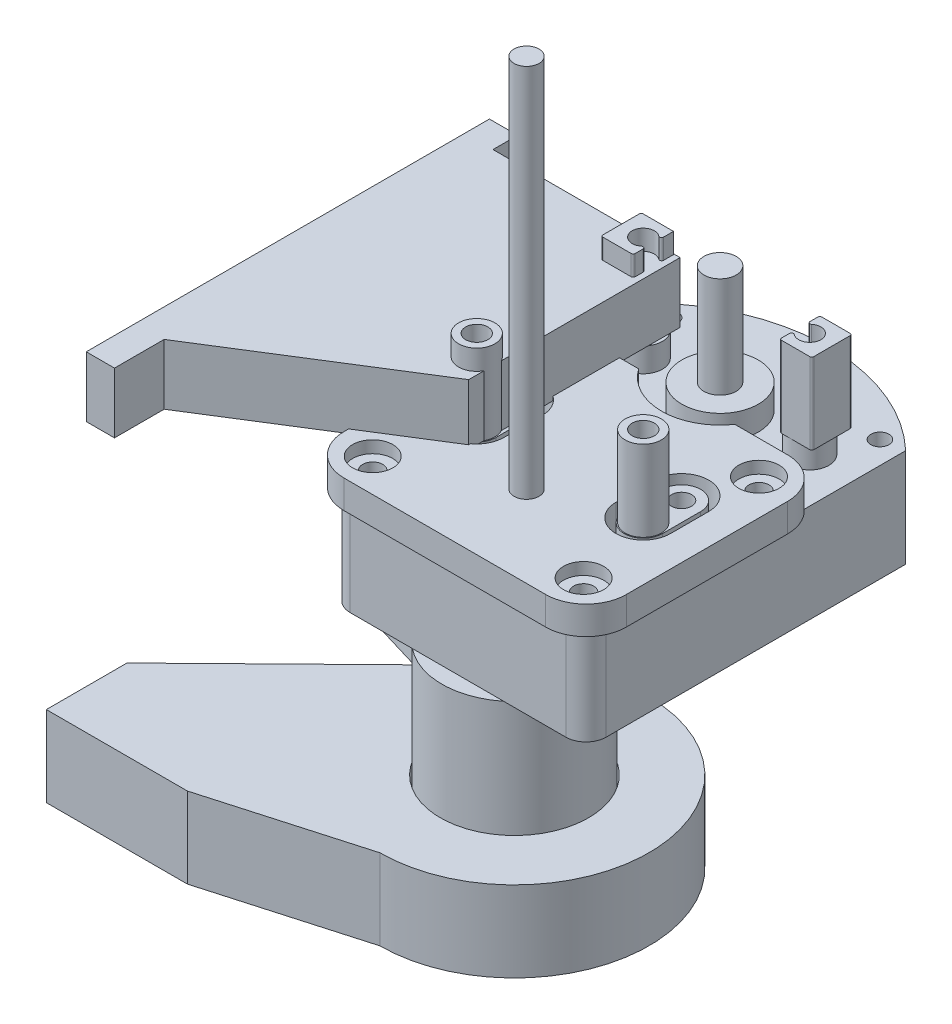
SolidWorks part; units mm, degrees
other "Gearbox Spacer rectangle"
other "Gearbox Spacer round "
ref_plane "Front Plane" through (0, 0, 0) normal (0, 0, 1) x (1, 0, 0)
ref_plane "Top Plane" through (0, 0, 0) normal (0, 1, 0) x (1, 0, 0)
ref_plane "Right Plane" through (0, 0, 0) normal (1, 0, 0) x (0, 0, -1)
sketch "Sketch1" plane through (0, 0, 0) normal (0, 1, 0) x (1, 0, 0)
  line L0 (31.75, -46) -> (31.75, 46)
  line L1 (31.75, -46) -> (-31.75, -46)
  line L2 (31.75, -46) -> (31.75, 46)
  line L3 (31.75, 46) -> (-31.75, 46)
  line L4 (-31.75, -46) -> (-31.75, 46)
  line L5 (0, 46) -> (0, -46) construction
  line L6 (31.75, 0) -> (-31.75, 0) construction
  line L7 (-31.75, -46) -> (-31.75, 46)
  circle A0 centre (-26.15, -41) radius 2.25
  circle A1 centre (-26.15, 2.5) radius 2.25
  circle A2 centre (-26.15, 32.5) radius 2.25
  circle A3 centre (26.15, 32.5) radius 2.25
  circle A4 centre (26.15, 2.5) radius 2.25
  circle A5 centre (26.15, -41) radius 2.25
  point P0 (0, 0)
  dimension "D3" = 4.5
  dimension "D1" = 63.5
  dimension "D2" = 92
  dimension "D4" = 52.3
  dimension "D5" = 5
  dimension "D6" = 43.5
  dimension "D7" = 30
extrude "Boss-Extrude1" add sketch "Sketch1" along normal blind 24.4 contours L4 L1 L0 L3 A4 A0 A1 A2 A3 A5
sketch "Sketch2" plane through (0, 24.4, 0) normal (0, 1, 0) x (1, 0, 0)
  line L0 (-20.65, -11.2) -> (-20.65, -20.7) construction
  line L1 (-15.9, -11.2) -> (-15.9, -20.7)
  line L2 (-25.4, -11.2) -> (-25.4, -20.7)
  line L3 (0, 0) -> (0, 46) construction
  line L4 (31.75, 46) -> (-31.75, 46) construction
  line L5 (0, 0) -> (-31.75, 0) construction
  line L6 (-31.75, -46) -> (-31.75, 46) construction
  line L7 (31.75, -46) -> (-31.75, -46) construction
  line L8 (20.65, -11.2) -> (20.65, -20.7) construction
  line L9 (15.9, -11.2) -> (15.9, -20.7)
  line L10 (25.4, -11.2) -> (25.4, -20.7)
  arc A0 (-15.9, -11.2) -> (-25.4, -11.2) centre (-20.65, -11.2) ccw
  arc A1 (-25.4, -20.7) -> (-15.9, -20.7) centre (-20.65, -20.7) ccw
  circle A2 centre (-20.65, 20.6) radius 4.75
  circle A3 centre (-20.65, -11.2) radius 2.5
  circle A4 centre (-20.65, -20.7) radius 2.5
  circle A5 centre (-20.65, 20.6) radius 2.5
  circle A6 centre (0, 19) radius 9.5
  circle A7 centre (0, 19) radius 4
  circle A8 centre (20.65, 20.6) radius 2.5
  circle A9 centre (20.65, -20.7) radius 2.5
  circle A10 centre (20.65, -11.2) radius 2.5
  circle A11 centre (20.65, 20.6) radius 4.75
  arc A12 (15.9, -11.2) -> (25.4, -11.2) centre (20.65, -11.2) cw
  arc A13 (25.4, -20.7) -> (15.9, -20.7) centre (20.65, -20.7) cw
  point P2 (-20.65, -15.95)
  point P39 (20.65, -15.95)
  dimension "D1" = 65
  dimension "D7" = 8
  dimension "D8" = 19
  dimension "D9" = 5
  dimension "D10" = 9.5
  dimension "D11" = 4.75
  dimension "D2" = 41.3
  dimension "D3" = 9.5
  dimension "D4" = 31.8
  dimension "D5" = 1.6
  dimension "D6" = 27
extrude "Boss-Extrude2" add sketch "Sketch2" along normal blind 6
sketch "Sketch3" plane through (0, 24.4, 0) normal (0, 1, 0) x (1, 0, 0)
  circle A1 centre (0, 19) radius 4
  circle A2 centre (0, 19) radius 4
  dimension "D1" = 0
extrude "Boss-Extrude3" add sketch "Sketch3" along normal blind 31
fillet "Fillet1" radius 5 2 edges at (31.75, 12.2, 46) (-31.75, 12.2, 46)
sketch "Sketch5" plane through (0, 24.4, 0) normal (0, 1, 0) x (1, 0, 0)
  line L0 (-31.75, -29) -> (31.75, -29) construction
  line L4 (31.75, -41) -> (31.75, 46) construction
  line L5 (-31.75, -41) -> (-31.75, 46) construction
  circle A0 centre (0, -29) radius 3.1
  circle A1 centre (0, 19) radius 15 construction
  circle A2 centre (0, -29) radius 33 construction
  dimension "D1" = 6.2
  dimension "D2" = 66
  dimension "D3" = 30
extrude "Boss-Extrude4" add sketch "Sketch5" along normal blind 100 separate body
sketch "Sketch6" plane through (0, 0, 0) normal (0, -1, 0) x (1, 0, 0)
  line L0 (-21.8301, 50) -> (22.1571, 50) construction
  line L1 (31.75, -46) -> (-31.75, -46) construction
  line L2 (0, 0) -> (0, 46) construction
  line L3 (26.75, 46) -> (-26.75, 46) construction
  circle A0 centre (0, 32) radius 18
  dimension "D1" = 96
  dimension "D2" = 36
extrude "Boss-Extrude5" add sketch "Sketch6" along normal blind 57
sketch "Sketch7" plane through (0, 24.4, 0) normal (0, 1, 0) x (1, 0, 0)
  line L1 (31.75, 33.2857) -> (31.75, 46)
  line L2 (31.75, -41) -> (31.75, 46) construction
  line L5 (-26.75, -46) -> (26.75, -46)
  line L6 (31.75, -41) -> (31.75, 46)
  line L7 (31.75, 46) -> (-31.75, 46)
  line L8 (-31.75, 46) -> (-31.75, -41)
  line L11 (31.75, 46) -> (-31.75, 46)
  line L12 (-31.75, 46) -> (-31.75, 33.2857)
  arc A1 (31.75, 33.2857) -> (-31.75, 33.2857) centre (0, 0) ccw
  arc A3 (26.75, -46) -> (31.75, -41) centre (26.75, -41) ccw
  arc A4 (-31.75, -41) -> (-26.75, -46) centre (-26.75, -41) ccw
  line M22 (31.75, -41) -> (31.75, 46)
  line M23 (31.75, 46) -> (-31.75, 46)
  line M24 (-31.75, 46) -> (-31.75, -41)
  dimension "D1" = 0
extrude "Cut-Extrude1" cut sketch "Sketch7" against normal up to next (24.4 mm away) contours A1 L11 M24 | A1 M22 M23
sketch "Sketch8" plane through (0, 30.4, 0) normal (0, 1, 0) x (1, 0, 0)
  line L0 (-16.6991, 25.7895) -> (-16.6991, -26.6457)
  line L1 (-16.6991, -26.6457) -> (-63.11, -55.7757)
  line L2 (-63.11, -55.7757) -> (-63.11, -68.0986)
  line L3 (-63.11, -68.0986) -> (-70.11, -68.0986)
  line L4 (-70.11, -68.0986) -> (-70.11, 31.9014)
  line L5 (-70.11, 31.9014) -> (-63.11, 31.9014)
  line L6 (-63.11, 31.9014) -> (-63.11, 25.7895)
  line L7 (-63.11, 25.7895) -> (-16.6991, 25.7895)
  line L8 (-31.75, -41) -> (-31.75, 33.2857) construction
  dimension "D1" = 38.36
  dimension "D2" = 7
  dimension "D3" = 100
extrude "Boss-Extrude6" add sketch "Sketch8" along normal blind 15 separate body
ref_plane "Plane1" through (0, -28.5, 0) normal (0, -1, 0) x (-1, 0, 0)
sketch "Sketch9" plane through (0, -28.5, 0) normal (0, -1, 0) x (-1, 0, 0)
  line L0 (25.1492, -10.0586) -> (72.11, -56)
  line L1 (72.11, -56) -> (72.11, -76)
  line L2 (72.11, -76) -> (37.11, -76)
  line L3 (72.11, 24) -> (72.11, 4)
  line L4 (37.11, -76) -> (0, -65.4)
  line L5 (72.11, 4) -> (25.1492, -10.0586)
  line L6 (72.11, 24) -> (42.2816, 24)
  line L7 (42.2816, 24) -> (0, 1.4)
  circle A0 centre (0, -32) radius 18.4
  arc A1 (0, 1.4) -> (0, -65.4) centre (0, -32) ccw
  circle A2 centre (0, -32) radius 18 construction
  dimension "D1" = 0.4
  dimension "D2" = 15
  dimension "D3" = 72.11
  dimension "D4" = 44
  dimension "D5" = 35
  dimension "D6" = 20
  dimension "D7" = 36
  dimension "D8" = 20
extrude "Boss-Extrude7" add sketch "Sketch9" along normal blind 20 separate body
sketch "Sketch11" plane through (0, 24.4, 0) normal (0, 1, 0) x (1, 0, 0)
  circle A0 centre (-26.15, 2.5) radius 4.85
  circle A1 centre (26.15, 2.5) radius 4.85
  circle A2 centre (-26.15, -41) radius 4.85
  circle A3 centre (26.15, -41) radius 4.85
  circle A4 centre (26.15, 2.5) radius 2.25 construction
  circle A5 centre (26.15, -41) radius 2.25 construction
  circle A6 centre (-26.15, -41) radius 2.25 construction
  circle A7 centre (-26.15, 2.5) radius 2.25 construction
  circle A8 centre (26.15, 2.5) radius 2.25
  circle A9 centre (26.15, -41) radius 2.25
  circle A10 centre (-26.15, -41) radius 2.25
  circle A11 centre (-26.15, 2.5) radius 2.25
  dimension "D1" = 9.7
extrude "Boss-Extrude8" add sketch "Sketch11" along normal blind 1
sketch "Sketch10" plane through (0, 24.4, 0) normal (0, 1, 0) x (1, 0, 0)
  line L0 (32, -19.25) -> (-31.75, -19.25) construction
  line L1 (0, -46.85) -> (0, 0) construction
  line L2 (-31.75, -41) -> (-31.75, 33.2857) construction
  line L3 (-11.9242, 10.75) -> (-35, 10.75)
  line L4 (35, -49.25) -> (-35, -49.25)
  line L5 (13.9, -11.2) -> (13.9, -20.7)
  line L6 (27.4, -20.7) -> (27.4, -11.2)
  line L7 (13.9, -11.2) -> (13.9, -20.7)
  line L8 (27.4, -20.7) -> (27.4, -11.2)
  line L9 (32, 2.5) -> (32, -41) construction
  line L10 (26.15, -46.85) -> (-26.15, -46.85) construction
  line L11 (-27.4, -11.2) -> (-27.4, -20.7)
  line L12 (-13.9, -20.7) -> (-13.9, -11.2)
  line L13 (-27.4, -11.2) -> (-27.4, -20.7)
  line L14 (-13.9, -20.7) -> (-13.9, -11.2)
  line L15 (35, -49.25) -> (35, 10.75)
  line L16 (35, 10.75) -> (11.9242, 10.75)
  line L17 (-35, -49.25) -> (-35, 10.75)
  line L19 (35, -19.25) -> (-35, -19.25) construction
  circle A0 centre (0, -29) radius 8.5
  circle A1 centre (-26.15, 2.5) radius 5.85
  circle A2 centre (26.15, 2.5) radius 5.85
  circle A3 centre (26.15, -41) radius 5.85
  circle A4 centre (-26.15, -41) radius 5.85
  circle A5 centre (-26.15, -41) radius 4.85 construction
  circle A6 centre (-26.15, -41) radius 2.25 construction
  circle A7 centre (26.15, -41) radius 2.25 construction
  circle A8 centre (26.15, 2.5) radius 2.25 construction
  circle A9 centre (-26.15, 2.5) radius 2.25 construction
  circle A10 centre (-26.15, -41) radius 2.25
  circle A11 centre (26.15, -41) radius 2.25
  circle A12 centre (26.15, 2.5) radius 2.25
  circle A13 centre (-26.15, 2.5) radius 2.25
  circle A16 centre (0, 19) radius 14.5
  arc A17 (-11.9242, 10.75) -> (11.9242, 10.75) centre (0, 19) ccw
  arc A18 (27.4, -11.2) -> (13.9, -11.2) centre (20.65, -11.2) ccw
  arc A19 (13.9, -20.7) -> (27.4, -20.7) centre (20.65, -20.7) ccw
  arc A20 (27.4, -11.2) -> (13.9, -11.2) centre (20.65, -11.2) ccw
  arc A21 (13.9, -20.7) -> (27.4, -20.7) centre (20.65, -20.7) ccw
  arc A24 (-13.9, -11.2) -> (-27.4, -11.2) centre (-20.65, -11.2) ccw
  arc A25 (-27.4, -20.7) -> (-13.9, -20.7) centre (-20.65, -20.7) ccw
  arc A26 (-13.9, -11.2) -> (-27.4, -11.2) centre (-20.65, -11.2) ccw
  arc A27 (-27.4, -20.7) -> (-13.9, -20.7) centre (-20.65, -20.7) ccw
  point P44 (0.125, -19.25)
  circle M7 centre (0, 19) radius 9.5
  line M19 (31.75, -41) -> (31.75, 33.2857)
  line M21 (-31.75, 33.2857) -> (-31.75, -41)
  line M23 (-26.75, -46) -> (26.75, -46)
  dimension "D1" = 17
  dimension "D2" = 1
  dimension "D5" = 70
  dimension "D6" = 60
  dimension "D3" = 2
  dimension "D4" = 2
  dimension "D7" = 5
extrude "Boss-Extrude9" add sketch "Sketch10" along normal blind 7 separate body contours A4 A3 A2 L16 A1 A27 L13 A26 L14 A21 L7 A20 L8 A0 M23 M19 M7 M21 | A4 A1 L16 L17 L4 L15 A2 A3 M21 M19 M23
sketch "Sketch12" plane through (0, 31.4, 0) normal (0, 1, 0) x (1, 0, 0)
  circle A1 centre (0, -29) radius 8.5 construction
  circle A2 centre (0, -29) radius 3.1
  circle A3 centre (0, -29) radius 8.5
  circle A4 centre (0, -29) radius 3.1 construction
extrude "Boss-Extrude10" add sketch "Sketch12" against normal blind 1
fillet "Fillet2" radius 10 4 edges at (35, 27.9, -10.75) (35, 27.9, 49.25) (-35, 27.9, 49.25) (-35, 27.9, -10.75)
sketch "Sketch13" plane through (0, 31.4, 0) normal (0, 1, 0) x (1, 0, 0)
  circle A1 centre (26.15, 2.5) radius 5.85 construction
  circle A2 centre (-26.15, 2.5) radius 5.85 construction
  circle A3 centre (-26.15, 2.5) radius 5.85
  circle A4 centre (26.15, 2.5) radius 5.85
  circle A5 centre (-26.15, -41) radius 5.85 construction
  circle A6 centre (26.15, -41) radius 5.85 construction
  circle A7 centre (-26.15, -41) radius 5.85
  circle A8 centre (26.15, -41) radius 5.85
  circle A9 centre (-26.15, -41) radius 2.5
  circle A10 centre (26.15, -41) radius 2.5
  circle A11 centre (26.15, 2.5) radius 2.5
  circle A12 centre (-26.15, 2.5) radius 2.5
  dimension "D1" = 5
extrude "Boss-Extrude11" add sketch "Sketch13" against normal up to surface (6 mm away) up to face at (-26.15, 25.4, 45.85)
sketch "Sketch14" plane through (0, 30.4, 0) normal (0, 1, 0) x (1, 0, 0)
  circle A0 centre (20.65, -20.7) radius 4.5
  circle A1 centre (-20.65, -20.7) radius 4.5
  circle A2 centre (20.65, -20.7) radius 2.75
  circle A3 centre (-20.65, -20.7) radius 2.75
  dimension "D1" = 5.5
  dimension "D2" = 9
extrude "Boss-Extrude12" add sketch "Sketch14" along normal blind 20 separate body
sketch "Sketch15" plane through (0, 30.4, 0) normal (0, 1, 0) x (1, 0, 0)
  line L0 (-18.15, 24.6389) -> (-18.15, 21.7456)
  line L1 (-18.15, 19.4544) -> (-18.15, 16.5611)
  line L2 (0, 0) -> (0, 46) construction
  line L5 (-18.15, 24.6389) -> (-18.15, 25.6)
  line L6 (-18.15, 25.6) -> (-26.15, 25.6)
  line L7 (-26.15, 25.6) -> (-26.15, 15.6)
  line L8 (-26.15, 15.6) -> (-18.15, 15.6)
  line L9 (-18.15, 15.6) -> (-18.15, 16.5611)
  line L10 (-20.65, 20.6) -> (-23.15, 20.6) construction
  line L11 (20.65, 20.6) -> (23.15, 20.6) construction
  line L12 (18.15, 15.6) -> (18.15, 16.5611)
  line L13 (26.15, 15.6) -> (18.15, 15.6)
  line L14 (26.15, 25.6) -> (26.15, 15.6)
  line L15 (18.15, 25.6) -> (26.15, 25.6)
  line L16 (18.15, 24.6389) -> (18.15, 25.6)
  line L17 (18.15, 19.4544) -> (18.15, 16.5611)
  line L18 (18.15, 24.6389) -> (18.15, 21.7456)
  arc A0 (-18.15, 21.7456) -> (-18.15, 19.4544) centre (-20.65, 20.6) ccw
  circle A2 centre (-20.65, 20.6) radius 4.75 construction
  arc A3 (31.75, 33.2857) -> (-31.75, 33.2857) centre (0, 0) ccw construction
  circle A6 centre (-20.65, 20.6) radius 2.5 construction
  circle A7 centre (-20.65, 20.6) radius 2.5 construction
  arc A8 (18.15, 21.7456) -> (18.15, 19.4544) centre (20.65, 20.6) cw
  dimension "D1" = 5.5
  dimension "D2" = 2.5
  dimension "D3" = 10
  dimension "D4" = 8
extrude "Boss-Extrude13" add sketch "Sketch15" along normal blind 20 separate body
fillet "Fillet3" radius 0.5 5 edges at (-18.15, 40.4, -21.7456) (-18.15, 40.4, -19.4544) (-18.15, 40.4, -15.6) (-26.15, 40.4, -15.6) (-26.15, 40.4, -25.6)
fillet "Fillet4" radius 0.5 6 edges at (18.15, 40.4, -19.4544) (18.15, 40.4, -21.7456) (18.15, 40.4, -25.6) (26.15, 40.4, -25.6) (26.15, 40.4, -15.6) (18.15, 40.4, -15.6)
other "Save Bodies1"
sketch "Sketch16" plane through (0, 31.4, 0) normal (0, 1, 0) x (1, 0, 0)
  circle A0 centre (-26.15, 2.5) radius 5
  circle A1 centre (26.15, 2.5) radius 5
  circle A2 centre (26.15, -41) radius 5
  circle A3 centre (-26.15, -41) radius 5
  dimension "D1" = 10
extrude "Cut-Extrude2" cut sketch "Sketch16" against normal blind 3
sketch "Sketch17" plane through (0, 0, 0) normal (0, -1, 0) x (1, 0, 0)
  line L0 (-31.75, -4) -> (-69.84, -4) construction
  line L1 (-31.75, 41) -> (-31.75, -33.2857) construction
  line L2 (-21.15, 5) -> (-49.84, 5)
  line L3 (-69.84, -4) -> (-86.84, -4) construction
  line L4 (-69.84, -4) -> (-69.84, -21)
  line L5 (-69.84, -21) -> (-86.84, -21)
  line L6 (-86.84, -4) -> (-86.84, -21) construction
  line L11 (-49.84, 5) -> (-69.84, -4)
  line L12 (-21.15, 5) -> (-21.15, -40)
  line L13 (-21.15, -40) -> (-73.84, -40)
  line L14 (-86.84, -27) -> (-86.84, -21)
  line L15 (-26.15, -32.5) -> (-26.15, -2.5) construction
  line L16 (-73.84, -40) -> (-86.84, -27)
  line L17 (-26.15, -17.5) -> (-31.75, -17.5) construction
  circle A0 centre (-26.15, -2.5) radius 2.25 construction
  circle A1 centre (-26.15, -32.5) radius 2.25 construction
  circle A2 centre (-26.15, -32.5) radius 2.25
  circle A3 centre (-26.15, -2.5) radius 2.25
  point P17 (0, 0)
  point P21 (-95.44, -29.8705)
  point P22 (-95.44, -29.0399)
  dimension "D1" = 38.09
  dimension "D2" = 1.5
  dimension "D3" = 17
  dimension "D4" = 45
  dimension "D5" = 5
  dimension "D6" = 45
  dimension "D7" = 6
  dimension "D8" = 20
extrude "Boss-Extrude14" add sketch "Sketch17" along normal blind 8 separate body
sketch "Sketch18" plane through (0, -8, 0) normal (0, -1, 0) x (1, 0, 0)
  line L0 (-63.84, -1.3) -> (-63.84, -27)
  line L1 (-49.84, 5) -> (-69.84, -4) construction
  line L2 (-63.84, -27) -> (-86.84, -27)
  line L3 (-86.84, -27) -> (-86.84, -21)
  line L4 (-86.84, -21) -> (-69.84, -21)
  line L5 (-69.84, -21) -> (-69.84, -4)
  line L6 (-69.84, -4) -> (-63.84, -1.3)
  dimension "D1" = 6
extrude "Boss-Extrude15" add sketch "Sketch18" along normal blind 15
sketch "Sketch19" plane through (0, 0, -21) normal (0, 0, 1) x (1, 0, 0)
  line L0 (-86.84, -17) -> (-69.84, -17) construction
  line L1 (-86.84, -23) -> (-86.84, 0) construction
  line L2 (-69.84, -23) -> (-69.84, 0) construction
  line L3 (-69.84, -23) -> (-86.84, -23) construction
  circle A0 centre (-78.34, -17) radius 2.75
  dimension "D2" = 5.5
  dimension "D1" = 6
extrude "Cut-Extrude3" cut sketch "Sketch19" against normal up to next (6 mm away)
sketch "Sketch20" plane through (-69.84, 0, 0) normal (-1, 0, 0) x (0, 0, 1)
  line L0 (-21, -17) -> (-4, -17) construction
  line L1 (-21, -23) -> (-21, 0) construction
  line L2 (-4, -23) -> (-4, 0) construction
  line L3 (-4, -23) -> (-21, -23) construction
  circle A0 centre (-12.5, -17) radius 2.75
  dimension "D1" = 5.5
  dimension "D2" = 6
extrude "Cut-Extrude4" cut sketch "Sketch20" against normal up to next (6 mm away)
fillet "Fillet5" radius 3 2 edges at (-75.34, -8, -27) (-63.84, -8, -14.15)
fillet "Fillet6" radius 3 4 edges at (-69.84, -11.5, -4) (-86.84, -11.5, -21) (-21.15, -4, 5) (-21.15, -4, -40)
